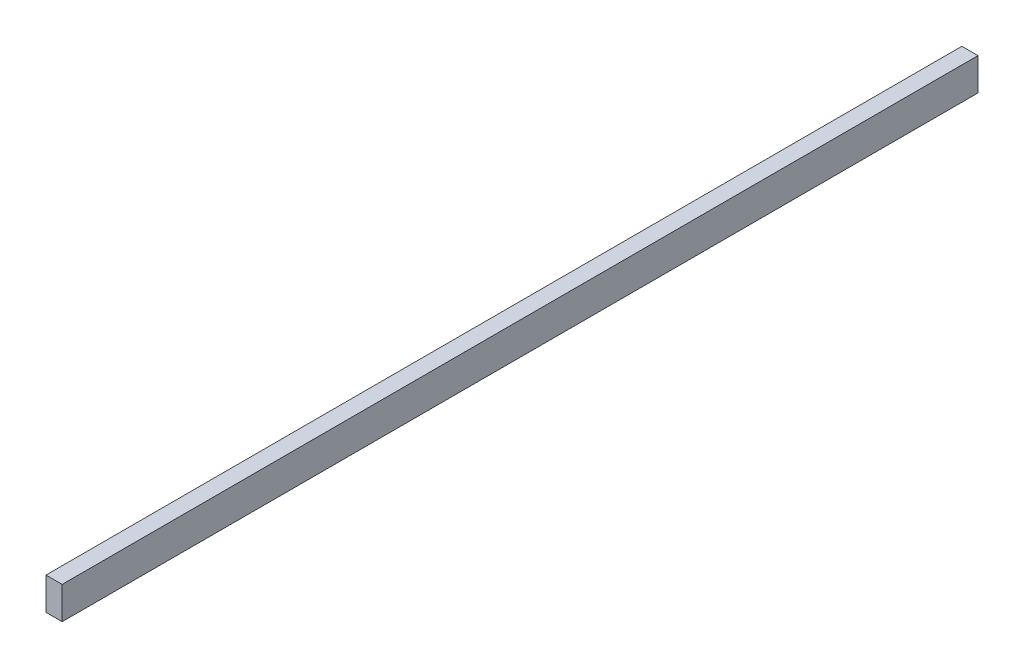
SolidWorks part; units mm, degrees
ref_plane "Front Plane" through (0, 0, 0) normal (0, 0, 1) x (1, 0, 0)
ref_plane "Top Plane" through (0, 0, 0) normal (0, 1, 0) x (1, 0, 0)
ref_plane "Right Plane" through (0, 0, 0) normal (1, 0, 0) x (0, 0, -1)
sketch "Sketch2" plane through (0, 0, 0) normal (0, 1, 0) x (1, 0, 0)
  line L1 (-0.75, -42.5) -> (0.75, -42.5)
  line L2 (-0.75, -42.5) -> (-0.75, 42.5)
  line L3 (-0.75, 42.5) -> (0.75, 42.5)
  line L4 (0.75, -42.5) -> (0.75, 42.5)
  line L5 (0, 42.5) -> (0, -42.5) construction
  line L6 (-0.75, 0) -> (0.75, 0) construction
  point P0 (0, 0)
  dimension "D1" = 1.5
  dimension "D2" = 85
extrude "Boss-Extrude1" add sketch "Sketch2" along normal blind 3
